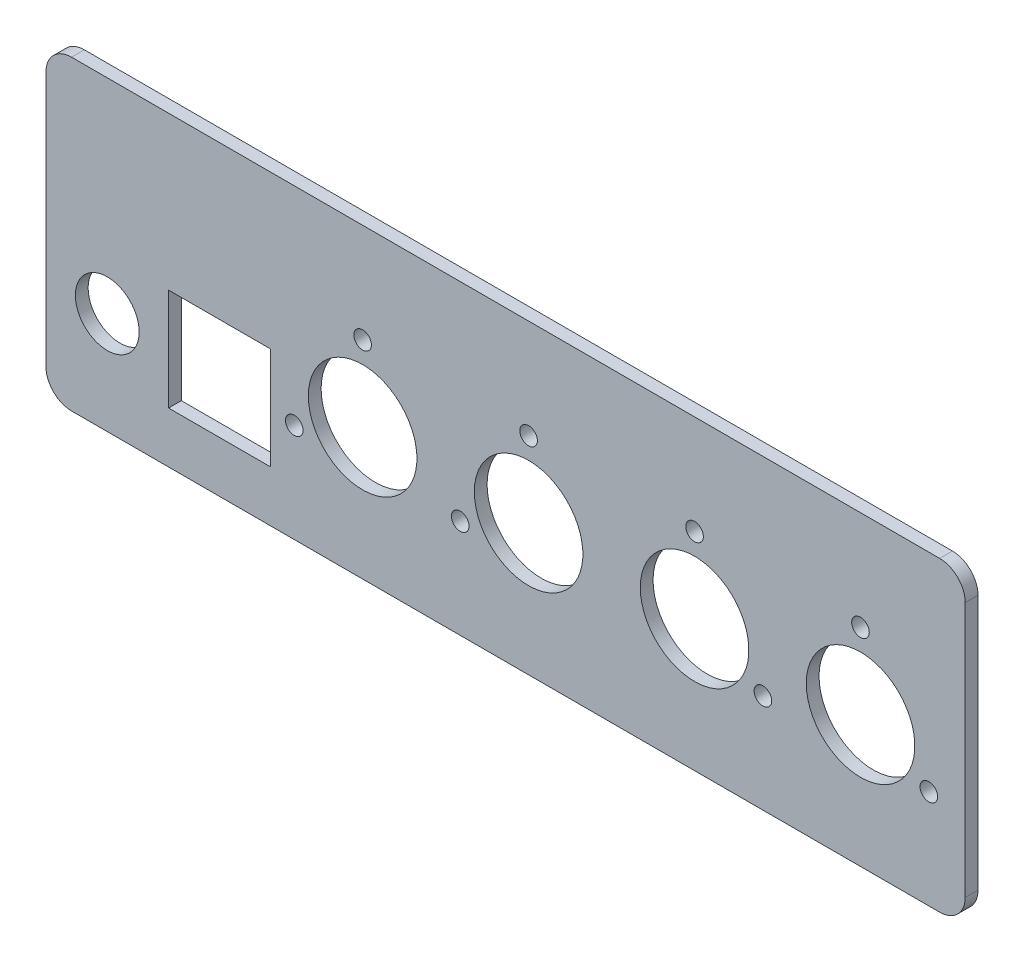
SolidWorks part; units mm, degrees
ref_plane "Front Plane" through (0, 0, 0) normal (0, 0, 1) x (1, 0, 0)
ref_plane "Top Plane" through (0, 0, 0) normal (0, 1, 0) x (1, 0, 0)
ref_plane "Right Plane" through (0, 0, 0) normal (1, 0, 0) x (0, 0, -1)
sketch "Sketch1" plane through (0, 0, 0) normal (0, 0, 1) x (1, 0, 0)
  line L0 (-52.8403, 24.358) -> (55.1097, 24.358)
  line L1 (-56.0153, 21.183) -> (-56.0153, -10.567)
  line L2 (-52.8403, -13.742) -> (55.1097, -13.742)
  line L3 (58.2847, 21.183) -> (58.2847, -10.567)
  arc A0 (-56.0153, -10.567) -> (-52.8403, -13.742) centre (-52.8403, -10.567) ccw
  arc A1 (55.1097, -13.742) -> (58.2847, -10.567) centre (55.1097, -10.567) ccw
  arc A2 (55.1097, 24.358) -> (58.2847, 21.183) centre (55.1097, 21.183) cw
  arc A3 (-52.8403, 24.358) -> (-56.0153, 21.183) centre (-52.8403, 21.183) ccw
  dimension "D1" = 3.175
  dimension "D2" = 38.1
  dimension "D3" = 114.3
extrude "Boss-Extrude1" add sketch "Sketch1" along normal blind 1.5875
sketch "Sketch2" plane through (0, 0, 0) normal (0, 0, -1) x (-1, 0, 0)
  line L0 (56.0153, 21.183) -> (56.0153, -10.567) construction
  line L1 (56.0153, 21.183) -> (56.0153, -10.567) construction
  line L2 (40.7753, 5.308) -> (28.0753, 5.308)
  line L3 (40.7753, 5.308) -> (40.7753, -7.392)
  line L4 (40.7753, -7.392) -> (28.0753, -7.392)
  line L5 (28.0753, 5.308) -> (28.0753, -7.392)
  line L6 (52.8403, -13.742) -> (-55.1097, -13.742) construction
  circle A0 centre (16.6453, 2.6079) radius 6.7488
  circle A1 centre (-3.9922, 2.6079) radius 6.7488
  circle A2 centre (-24.6297, 2.6079) radius 6.7488
  circle A3 centre (-45.2672, 2.6079) radius 6.7488
  circle A4 centre (48.3953, -1.042) radius 3.9687
  point P18 (40.7753, -1.042)
  dimension "D1" = 13.4976
  dimension "D9" = 7.9375
  dimension "D3" = 11.43
  dimension "D4" = 12.7
  dimension "D5" = 12.7
  dimension "D6" = 10
  dimension "D7" = 15.24
  dimension "D8" = 6.35
  dimension "D10" = 0
  dimension "D11" = 7.62
  dimension "D2" = 4
extrude "Cut-Extrude1" cut sketch "Sketch2" against normal blind 1.5875
sketch "Sketch3" plane through (0, 0, 1.5875) normal (0, 0, 1) x (1, 0, 0)
  line L3 (-56.0153, 21.183) -> (-56.0153, -10.567) construction
  line L4 (-52.8403, -13.742) -> (55.1097, -13.742) construction
  circle A0 centre (-16.6453, 12.0079) radius 1.0922
  circle A1 centre (3.9897, 12.0079) radius 1.0922
  circle A2 centre (24.6247, 12.0079) radius 1.0922
  circle A3 centre (-25.1453, -1.4421) radius 1.0922
  circle A4 centre (-4.5103, -1.4421) radius 1.0922
  circle A5 centre (33.1247, -1.4421) radius 1.0922
  circle A6 centre (45.2597, 12.0079) radius 1.0922
  circle A7 centre (53.7597, -1.4421) radius 1.0922
  point P20 (-50.4311, 11.2816)
  point P21 (-45.5141, 17.221)
  dimension "D5" = 2.1844
  dimension "D6" = 2.1844
  dimension "D7" = 2.1844
  dimension "D8" = 2.1844
  dimension "D9" = 2.1844
  dimension "D10" = 2.1844
  dimension "D11" = 2.1844
  dimension "D22" = 2.1844
  dimension "D1" = 20.635
  dimension "D2" = 20.635
  dimension "D3" = 20.635
  dimension "D12" = 20.635
  dimension "D13" = 37.635
  dimension "D14" = 20.635
  dimension "D15" = 30.87
  dimension "D16" = 39.37
  dimension "D17" = 13.45
  dimension "D18" = 13.45
  dimension "D19" = 13.45
  dimension "D20" = 13.45
  dimension "D21" = 12.3
extrude "Cut-Extrude2" cut sketch "Sketch3" against normal through all
sketch "Sketch5" plane through (0, 0, 1.5875) normal (0, 0, 1) x (1, 0, 0)
  line L1 (-56.0153, 24.358) -> (58.2847, 24.358)
  line L2 (-56.0153, 24.358) -> (-56.0153, -13.742)
  line L3 (-56.0153, -13.742) -> (58.2847, -13.742)
  line L4 (58.2847, 24.358) -> (58.2847, -13.742)
  line L5 (-75.0653, -20.4551) -> (77.3347, -20.4551)
  line L6 (-75.0653, -20.4551) -> (-75.0653, 30.3449)
  line L7 (-75.0653, 30.3449) -> (77.3347, 30.3449)
  line L8 (77.3347, -20.4551) -> (77.3347, 30.3449)
  circle A0 centre (-65.5403, 5.308) radius 2.3813
  circle A1 centre (67.8097, 5.308) radius 2.3813
  dimension "D3" = 4.7625
  dimension "D4" = 4.7625
  dimension "D1" = 152.4
  dimension "D2" = 50.8
